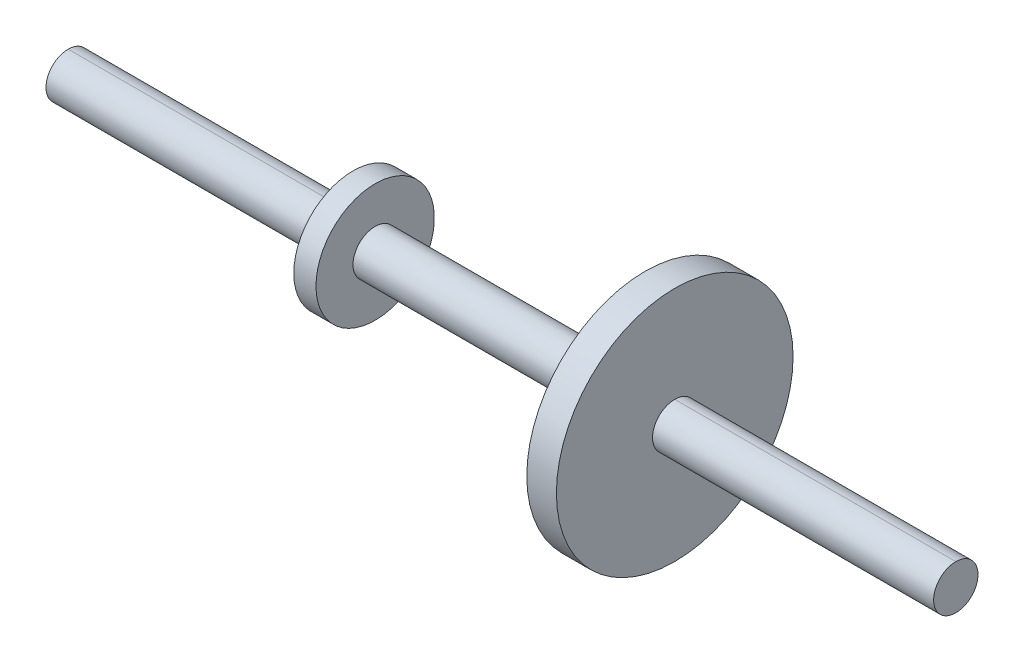
SolidWorks part; units mm, degrees
ref_plane "Front Plane" through (0, 0, 0) normal (0, 0, 1) x (1, 0, 0)
ref_plane "Top Plane" through (0, 0, 0) normal (0, 1, 0) x (1, 0, 0)
ref_plane "Right Plane" through (0, 0, 0) normal (1, 0, 0) x (0, 0, -1)
sketch "Sketch1" plane through (0, 0, 0) normal (0, 1, 0) x (1, 0, 0)
  line L0 (0, 0) -> (762, 0)
  line L1 (762, 0) -> (762, 19.05)
  line L2 (762, 19.05) -> (520.7, 19.05)
  line L3 (520.7, 19.05) -> (520.7, 101.6)
  line L4 (520.7, 101.6) -> (495.3, 101.6)
  line L5 (495.3, 101.6) -> (495.3, 19.05)
  line L6 (495.3, 19.05) -> (263.525, 19.05)
  line L7 (263.525, 19.05) -> (263.525, 50.8)
  line L8 (263.525, 50.8) -> (244.475, 50.8)
  line L9 (244.475, 50.8) -> (244.475, 19.05)
  line L10 (244.475, 19.05) -> (0, 19.05)
  line L11 (0, 19.05) -> (0, 0)
  point P3 (508, 101.6)
  point P14 (254, 50.8)
  dimension "D1" = 762
  dimension "D2" = 19.05
  dimension "D3" = 254
  dimension "D4" = 254
  dimension "D5" = 50.8
  dimension "D6" = 101.6
  dimension "D7" = 19.05
  dimension "D8" = 25.4
revolve "Revolve1" add sketch "Sketch1" angle 360 about L0
sketch "Sketch2" plane through (0, 0, 0) normal (0, 0, 1) x (1, 0, 0)
  line L0 (254, 50.8) -> (254, -50.8)
  line L1 (263.525, 50.8) -> (244.475, 50.8) construction
  line L2 (244.475, -50.8) -> (263.525, -50.8) construction
sketch "Sketch3" plane through (0, 0, 0) normal (0, 1, 0) x (1, 0, 0)
  line L0 (508, 101.6) -> (508, -101.6)
  line L1 (520.7, 101.6) -> (495.3, 101.6) construction
  line L2 (495.3, -101.6) -> (520.7, -101.6) construction
ref_plane "Plane1" through (0, -19.05, 0) normal (0, -1, 0) x (-1, 0, 0)
sketch "Sketch4" plane through (0, -19.05, 0) normal (0, -1, 0) x (-1, 0, 0)
  line L0 (0, -19.05) -> (0, 19.05) construction
  line L1 (0, -19.05) -> (0, 19.05)
  point P5 (0, 0)
split line "Split Line7"
sketch "Sketch5" plane through (0, -19.05, 0) normal (0, -1, 0) x (-1, 0, 0)
  line L0 (-762, 19.05) -> (-762, -19.05) construction
  line L1 (-762, 19.05) -> (-762, -19.05)
  point P2 (-762, 0)
split line "Split Line10"
ref_point "Point1"
ref_point "Point2"
ref_point "Point3"
ref_point "Point4"
